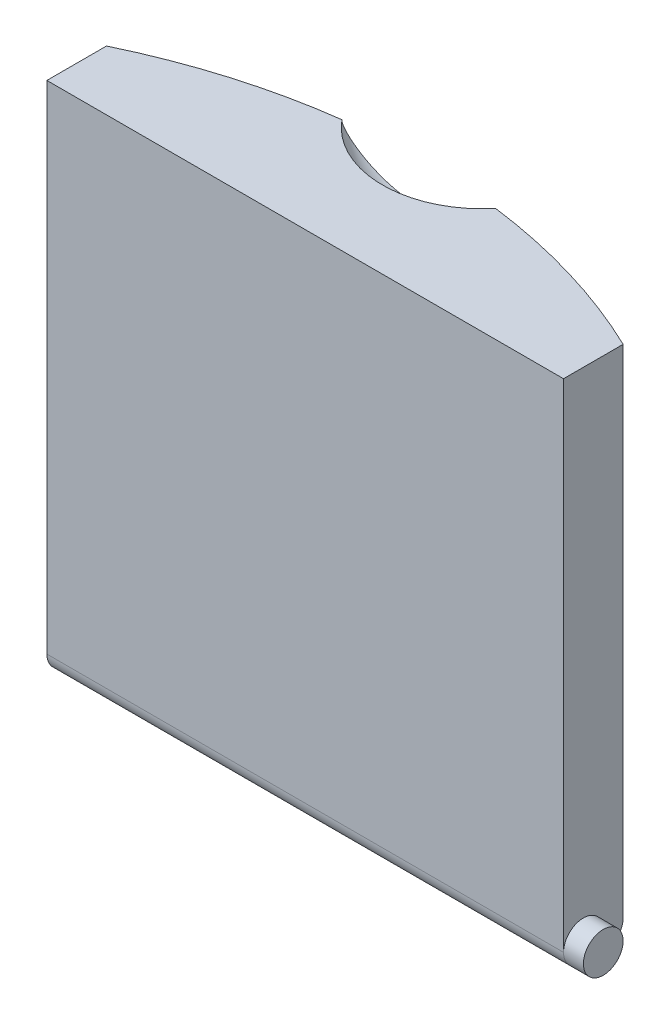
SolidWorks part; units mm, degrees
material "Custom Plastic"
ref_plane "Front Plane" through (0, 0, 0) normal (0, 0, 1) x (1, 0, 0)
ref_plane "Top Plane" through (0, 0, 0) normal (0, 1, 0) x (1, 0, 0)
ref_plane "Right Plane" through (0, 0, 0) normal (1, 0, 0) x (0, 0, -1)
sketch "Sketch1" plane through (0, 0, 0) normal (0, 0, 1) x (1, 0, 0)
  line L1 (-59.7037, 62.1111) -> (200.2963, 62.1111)
  line L2 (-59.7037, 62.1111) -> (-59.7037, -197.8889)
  line L3 (-59.7037, -197.8889) -> (200.2963, -197.8889)
  line L4 (200.2963, 62.1111) -> (200.2963, -197.8889)
  dimension "D1" = 260
  dimension "D2" = 260
extrude "Boss-Extrude1" add sketch "Sketch1" along normal blind 30
sketch "Sketch2" plane through (200.2963, 0, 0) normal (1, 0, 0) x (0, 0, -1)
  line L1 (0, -197.8889) -> (0, 62.1111) construction
  line L2 (-30, -197.8889) -> (0, -197.8889) construction
  circle A0 centre (-20, -187.8889) radius 10
  point P6 (-140.181, -116.2014)
  dimension "D1" = 20
  dimension "D2" = 10
extrude "Boss-Extrude2" add sketch "Sketch2" along normal blind 10
sketch "Sketch3" plane through (0, 62.1111, 0) normal (0, 1, 0) x (1, 0, 0)
  line L0 (200.2963, 0) -> (-59.7037, 0) construction
  line L1 (-59.7037, 0) -> (200.2963, 0)
  arc A0 (-59.7037, 0) -> (200.2963, 0) centre (70.2963, -270.3701) cw
extrude "Boss-Extrude3" add sketch "Sketch3" against normal blind 50
fillet "Fillet1" radius 10 2 edges at (70.2963, -197.8889, 30) (70.2963, -197.8889, 0)
ref_plane "Plane1" through (0, 0, -30) normal (0, 0, -1) x (-1, 0, 0)
sketch "Sketch5" plane through (0, 0, -30) normal (0, 0, -1) x (-1, 0, 0)
  line L0 (59.7037, 62.1111) -> (-200.2963, 62.1111) construction
  line L1 (-111.1301, 62.1111) -> (-29.4624, 62.1111)
  arc A0 (-111.1301, 62.1111) -> (-29.4624, 62.1111) centre (-70.2963, 33.2564) cw
  point P3 (-70.2963, 83.2564)
  point P6 (-70.2963, 62.1111)
revolve "Cut-Revolve1" cut sketch "Sketch5" angle 360 about L1
sketch "Sketch6" plane through (0, 0, -30) normal (0, 0, -1) x (-1, 0, 0)
  line L1 (-31.6498, 62.1111) -> (-108.9428, 62.1111) construction
  line L3 (-168.9143, 12.1111) -> (28.3217, 12.1111)
  arc A2 (-168.9143, 12.1111) -> (28.3217, 12.1111) centre (-70.2963, 213.9454) ccw
  point P5 (-70.2963, 62.1111)
  point P6 (-70.2963, 12.1111)
revolve "Cut-Revolve2" cut sketch "Sketch6" angle 360 about L3
